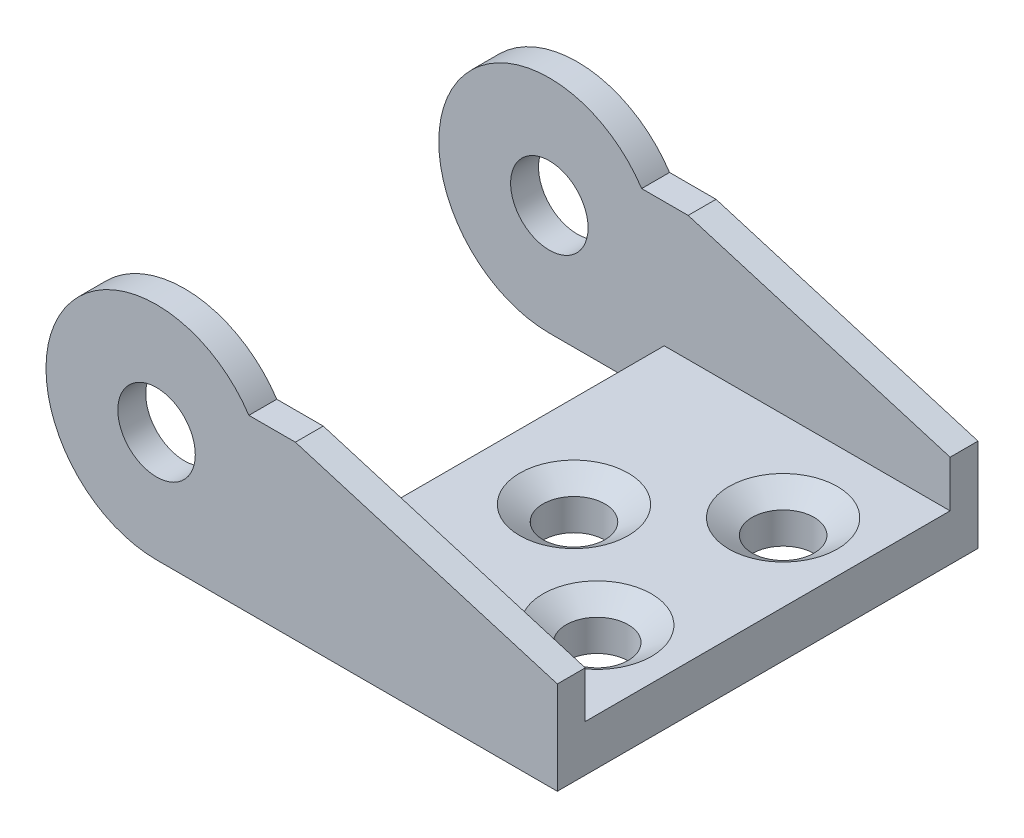
SolidWorks part; units mm, degrees
ref_plane "Front Plane" through (0, 0, 0) normal (0, 0, 1) x (1, 0, 0)
ref_plane "Top Plane" through (0, 0, 0) normal (0, 1, 0) x (1, 0, 0)
ref_plane "Right Plane" through (0, 0, 0) normal (1, 0, 0) x (0, 0, -1)
sketch "Sketch1" plane through (0, 0, 0) normal (1, 0, 0) x (0, 0, -1)
  line L0 (0, 14.27) -> (0, 0)
  line L1 (0, 0) -> (27.15, 0)
  line L2 (27.15, 0) -> (27.15, 14.27)
  line L3 (27.15, 14.27) -> (25.35, 14.27)
  line L4 (25.35, 14.27) -> (25.35, 3)
  line L5 (25.35, 3) -> (1.8, 3)
  line L6 (1.8, 3) -> (1.8, 14.27)
  line L7 (1.8, 14.27) -> (0, 14.27)
  dimension "D1" = 27.15
  dimension "D2" = 1.8
  dimension "D3" = 3
  dimension "D4" = 14.27
extrude "ProfileBoss-Extrude1" add sketch "Sketch1" along normal blind 33
sketch "Sketch2" plane through (0, 0, 0) normal (0, 0, 1) x (1, 0, 0)
  line L0 (13.0934, 11.06) -> (16.0934, 11.06)
  line L1 (16.0934, 11.06) -> (33, 6)
  line L2 (33, 14.27) -> (0, 14.27) construction
  line L3 (0, 14.27) -> (0, 0) construction
  line L4 (33, 14.27) -> (33, 0) construction
  line L5 (33, 6) -> (33, 0)
  line L6 (33, 0) -> (7.135, 0)
  line L7 (33, 0) -> (0, 0) construction
  arc A0 (13.0934, 11.06) -> (7.135, 0) centre (7.135, 7.135) ccw
  circle A1 centre (7.135, 7.135) radius 2.5
  dimension "D1" = 14.27
  dimension "D5" = 5
  dimension "D2" = 11.06
  dimension "D3" = 3
  dimension "D4" = 6
extrude "SideProfileCut-Extrude1" cut sketch "Sketch2" against normal through all flip side to cut
sketch "Sketch3" plane through (0, 3, 0) normal (0, 1, 0) x (1, 0, 0)
  line L0 (1.3204, 25.35) -> (14.55, 25.35)
  line L1 (33, 25.35) -> (1.3204, 25.35) construction
  line L2 (14.55, 25.35) -> (14.55, 22.2)
  line L3 (14.55, 22.2) -> (10.05, 22.2)
  line L4 (10.05, 22.2) -> (10.05, 4.95)
  line L5 (10.05, 4.95) -> (14.55, 4.95)
  line L6 (14.55, 4.95) -> (14.55, 1.8)
  line L7 (16.0934, 1.8) -> (13.0934, 1.8) construction
  line L8 (14.55, 1.8) -> (1.3204, 1.8)
  line L9 (1.3204, 1.8) -> (1.3204, 25.35)
  line L10 (33, 25.35) -> (33, 1.8) construction
  dimension "D1" = 22.95
  dimension "D2" = 4.5
  dimension "D3" = 3.15
extrude "BottomCut-Extrude2" cut sketch "Sketch3" against normal through all
sketch "DragLinkMountHolesSketch4" plane through (0, 3, 0) normal (0, 1, 0) x (1, 0, 0)
  line L0 (33, 25.35) -> (33, 1.8) construction
  line L1 (33, 0) -> (16.0934, 0) construction
  circle A0 centre (28, 19.575) radius 2
  circle A1 centre (28, 7.575) radius 2
  circle A2 centre (20.5, 13.575) radius 2
  dimension "D6" = 4
  dimension "D1" = 12
  dimension "D2" = 6
  dimension "D3" = 7.5
  dimension "D4" = 5
  dimension "D5" = 13.575
extrude "DragLinkMountHolesCut-Extrude3" cut sketch "DragLinkMountHolesSketch4" against normal through all
chamfer "Chamfer1" distance 1.5 angle 33 3 edges at (28, 3, -5.575) (28, 3, -17.575) (20.5, 3, -11.575)
sketch "Sketch4" plane through (0, 3, 0) normal (0, 1, 0) x (1, 0, 0)
  line L0 (10.05, 22.2) -> (14.55, 22.2) construction
  line L1 (10.05, 22.2) -> (14.55, 22.2)
  line L2 (10.05, 22.2) -> (10.05, 4.95)
  line L3 (10.05, 4.95) -> (14.55, 4.95)
  line L4 (14.55, 22.2) -> (14.55, 4.95)
  line L5 (10.05, 4.95) -> (10.05, 22.2) construction
extrude "DisableSwiivelRestrictionCut-Extrude4" cut sketch "Sketch4" against normal through all
equation "\"DragLinkDepth\"= 14.27mm"
equation "\"D4@Sketch1\"=\"DragLinkDepth\""
equation "\"DragLinkSideWallThickness\"= 1.8mm"
equation "\"D2@Sketch1\"=\"DragLinkSideWallThickness\""
equation "\"D5@DragLinkMountHolesSketch4\" = \"DragLinkHeight\" / 2"
equation "\"DragLinkHeight\" = 27.15mm"
equation "\"D1@Sketch1\"=\"DragLinkHeight\""
equation "\"DragLinkWidth\" = 33mm"
equation "\"D1@ProfileBoss-Extrude1\"=\"DragLinkWidth\""
equation "\"DragLinkMountHoleDiameter\" = 4mm"
